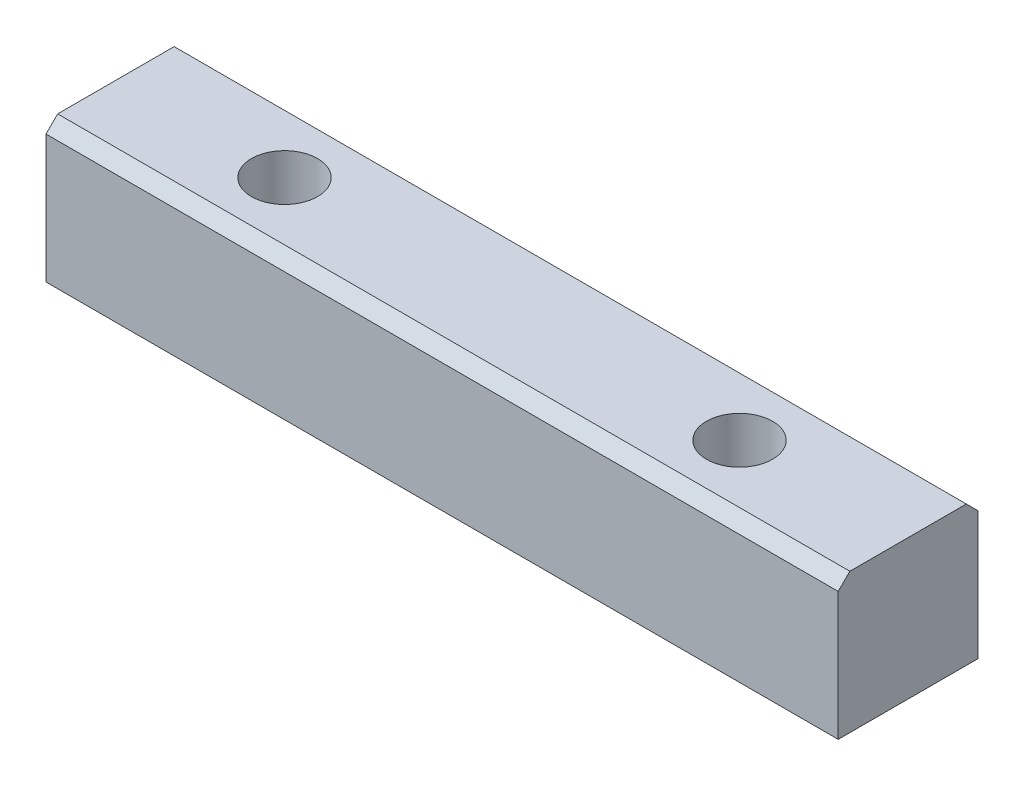
SolidWorks part; units mm, degrees
material "Low Carbon Steel"
ref_plane "Front Plane" through (0, 0, 0) normal (0, 0, 1) x (1, 0, 0)
ref_plane "Top Plane" through (0, 0, 0) normal (0, 1, 0) x (1, 0, 0)
ref_plane "Right Plane" through (0, 0, 0) normal (1, 0, 0) x (0, 0, -1)
sketch "Sketch1" plane through (0, 0, 0) normal (1, 0, 0) x (0, 0, -1)
  line L0 (-9.525, -9.525) -> (9.525, 9.525) construction
  line L1 (-9.525, 9.525) -> (9.525, 9.525)
  line L2 (-9.525, 9.525) -> (-9.525, -9.525)
  line L3 (-9.525, -9.525) -> (9.525, -9.525)
  line L4 (9.525, 9.525) -> (9.525, -9.525)
  dimension "D1" = 19.05
  dimension "D2" = 19.05
extrude "Boss-Extrude1" add sketch "Sketch1" along normal mid plane 107.95
hole_wizard "M8 Clearance Hole1" positions "Sketch3" profile "Sketch2" hole size "M8" standard "Peddi DIN" end condition through all
sketch "Sketch3" plane through (0, 9.525, 0) normal (0, 1, 0) x (1, 0, 0)
  line L0 (-31, 0) -> (31, 0) construction
  point P0 (-31, 0)
  point P2 (31, 0)
  dimension "D1" = 62
sketch "Sketch2" plane through (-31, 9.525, 0) normal (1, 0, 0) x (0, 0, 1)
  line L0 (0, 0) -> (0, 19.05)
  line L1 (0, 19.05) -> (4.5, 19.05)
  line L2 (4.5, 19.05) -> (4.5, 0)
  line L5 (4.5, 0) -> (0, 0)
  line L11 (0, -6.35) -> (0, 107.95) construction
  dimension "Thru Hole Dia." = 9
  dimension "Thru Hole Depth" = 19.05
chamfer "Chamfer1" distance 1.5875 angle 45 2 edges at (0, 9.525, -9.525) (0, 9.525, 9.525)
other "Freeze***"
